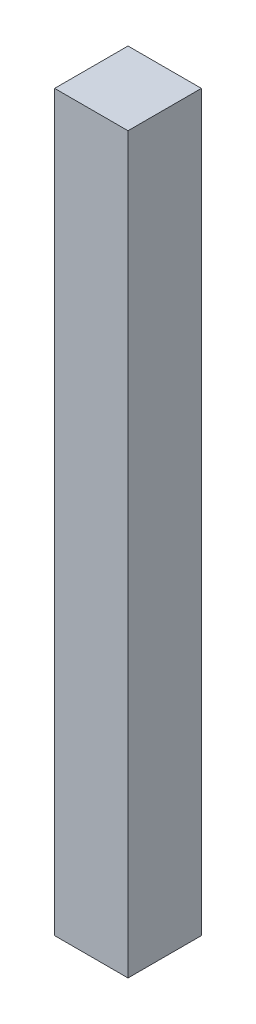
SolidWorks part; units mm, degrees
ref_plane "Front Plane" through (0, 0, 0) normal (0, 0, 1) x (1, 0, 0)
ref_plane "Top Plane" through (0, 0, 0) normal (0, 1, 0) x (1, 0, 0)
ref_plane "Right Plane" through (0, 0, 0) normal (1, 0, 0) x (0, 0, -1)
sketch "Sketch1" plane through (0, 0, 0) normal (0, 1, 0) x (1, 0, 0)
  line L1 (0, 0) -> (20, 0)
  line L2 (0, 0) -> (0, -20)
  line L3 (0, -20) -> (20, -20)
  line L4 (20, 0) -> (20, -20)
extrude "Boss-Extrude1" add sketch "Sketch1" along normal blind 200
